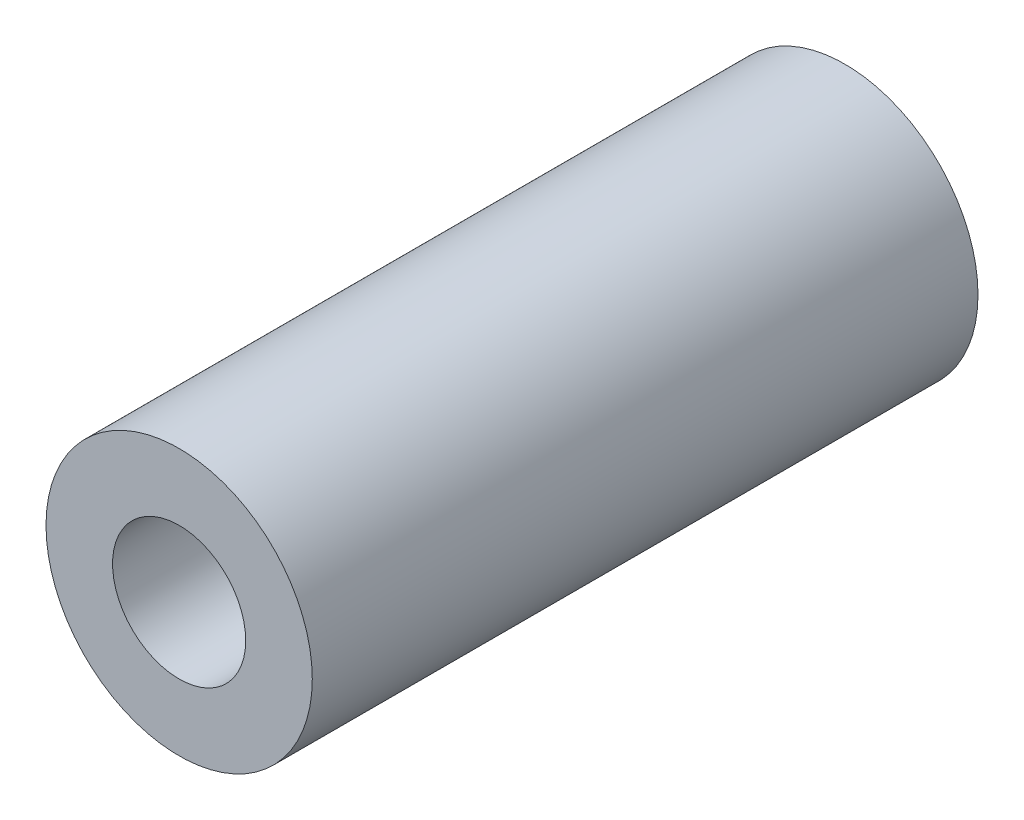
SolidWorks part; units mm, degrees
ref_plane "前视基准面" through (0, 0, 0) normal (0, 0, 1) x (1, 0, 0)
ref_plane "上视基准面" through (0, 0, 0) normal (0, 1, 0) x (1, 0, 0)
ref_plane "右视基准面" through (0, 0, 0) normal (1, 0, 0) x (0, 0, -1)
sketch "草图1" plane through (0, 0, 0) normal (0, 0, 1) x (1, 0, 0)
  circle A0 centre (0, 0) radius 4
  circle A1 centre (0, 0) radius 2
  point P5 (0.2592, 0)
  dimension "D1" = 4
  dimension "D2" = 8
extrude "凸台-拉伸1" add sketch "草图1" along normal mid plane 20
